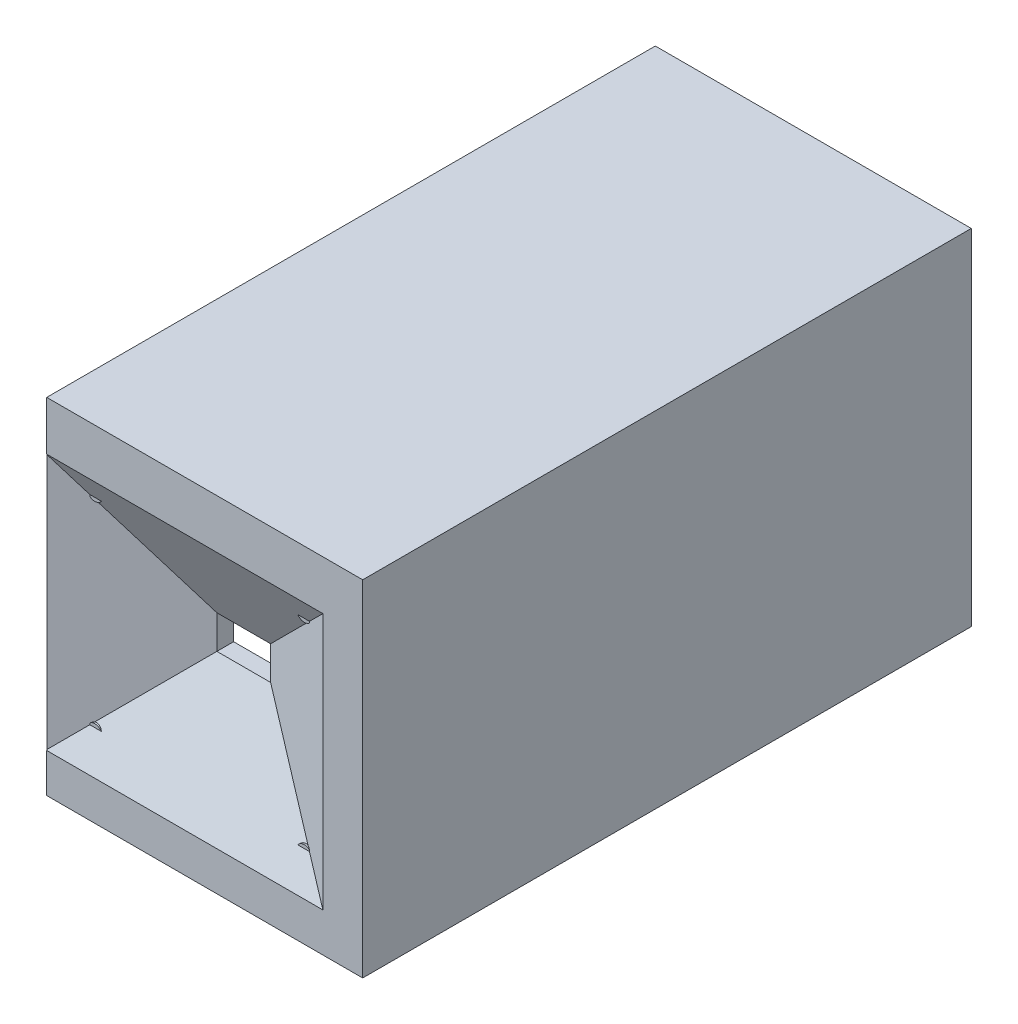
SolidWorks part; units mm, degrees
ref_plane "Front Plane" through (0, 0, 0) normal (0, 0, 1) x (1, 0, 0)
ref_plane "Top Plane" through (0, 0, 0) normal (0, 1, 0) x (1, 0, 0)
ref_plane "Right Plane" through (0, 0, 0) normal (1, 0, 0) x (0, 0, -1)
sketch "Sketch1" plane through (0, 0, 0) normal (0, 0, 1) x (1, 0, 0)
  line L10 (0, 0) -> (13.075, 0)
  line L15 (-13.575, -13.5) -> (-13.575, 13.5)
  line L16 (-13.575, 13.5) -> (13.575, 13.5)
  line L21 (13.575, -13.5) -> (13.575, 13.5)
  line L22 (-13.575, -13.5) -> (13.575, -13.5)
  line L28 (-12.425, -3.5) -> (-12.425, 3.5)
  line L29 (-12.425, 3.5) -> (-7.125, 3.5)
  line L30 (-7.125, -3.5) -> (-7.125, 3.5)
  line L31 (-12.425, -3.5) -> (-7.125, -3.5)
  line L32 (12.425, -3.5) -> (7.125, -3.5)
  line L33 (7.125, -3.5) -> (7.125, 3.5)
  line L34 (12.425, -3.5) -> (12.425, 3.5)
  line L35 (12.425, 3.5) -> (7.125, 3.5)
  line L36 (-2.65, -1.65) -> (-2.65, 1.65)
  line L37 (-2.65, 1.65) -> (2.65, 1.65)
  line L38 (2.65, -1.65) -> (2.65, 1.65)
  line L39 (-2.65, -1.65) -> (2.65, -1.65)
  circle A5 centre (10.325, 10.25) radius 0.762
  circle A6 centre (10.325, -10.25) radius 0.762
  circle A7 centre (-10.325, -10.25) radius 0.762
  circle A8 centre (-10.325, 10.25) radius 0.762
  point P0 (0, 0)
  point P16 (0, 0)
  point P31 (-9.775, 0)
  dimension "D10" = 1.524
  dimension "D11" = 1.524
  dimension "D12" = 1.524
  dimension "D13" = 1.524
  dimension "D18" = 13.075
ref_plane "Plane1" through (0, 0, 0) normal (0, 0, 1) x (1, 0, 0)
sketch "Sketch2" plane through (0, 0, 0) normal (0, 0, 1) x (1, 0, 0)
  line L0 (-16.575, 16.5) -> (-16.575, -16.5)
  line L5 (-16.575, -16.5) -> (16.575, -16.5)
  line L6 (16.575, 16.5) -> (16.575, -16.5)
  line L7 (-16.575, 16.5) -> (16.575, 16.5)
extrude "Boss-Extrude1" add sketch "Sketch2" along normal blind 7.5
ref_plane "Plane2" through (0, 0, 0) normal (0, 0, 1) x (1, 0, 0)
sketch "Sketch3" plane through (0, 0, 0) normal (0, 0, 1) x (1, 0, 0)
  circle A0 centre (10.325, 10.25) radius 0.762
  circle A1 centre (-10.325, 10.25) radius 0.762
  circle A2 centre (10.325, -10.25) radius 0.762
  circle A3 centre (-10.325, -10.25) radius 0.762
  dimension "D1" = 1.524
  dimension "D2" = 1.524
  dimension "D3" = 1.524
  dimension "D4" = 1.524
extrude "Cut-Extrude1" cut sketch "Sketch3" along normal blind 6
ref_plane "Plane3" through (0, 0, 0) normal (0, 0, 1) x (1, 0, 0)
sketch "Sketch4" plane through (0, 0, 0) normal (0, 0, 1) x (1, 0, 0)
  line L1 (12.425, -3.5) -> (7.125, -3.5)
  line L2 (12.425, -3.5) -> (12.425, 3.5)
  line L3 (12.425, 3.5) -> (7.125, 3.5)
  line L4 (7.125, -3.5) -> (7.125, 3.5)
  line L5 (-7.125, -3.5) -> (-12.425, -3.5)
  line L6 (-7.125, -3.5) -> (-7.125, 3.5)
  line L7 (-7.125, 3.5) -> (-12.425, 3.5)
  line L8 (-12.425, -3.5) -> (-12.425, 3.5)
extrude "Cut-Extrude2" cut sketch "Sketch4" along normal blind 3.4
ref_plane "Plane4" through (0, 0, 0) normal (0, 0, 1) x (1, 0, 0)
sketch "Sketch5" plane through (0, 0, 0) normal (0, 0, 1) x (1, 0, 0)
  line L1 (8.5467, -12.7134) -> (-8.766, -12.7134)
  line L2 (8.5467, -12.7134) -> (8.5467, -10.9049)
  line L3 (8.5467, -10.9049) -> (-8.766, -10.9049)
  line L4 (-8.766, -12.7134) -> (-8.766, -10.9049)
extrude "Cut-Extrude3" cut sketch "Sketch5" along normal blind 2
ref_plane "Plane5" through (0, 0, 0) normal (0, 0, 1) x (1, 0, 0)
sketch "Sketch6" plane through (0, 0, 0) normal (0, 0, 1) x (1, 0, 0)
  line L1 (2.65, -1.65) -> (-2.65, -1.65)
  line L2 (2.65, -1.65) -> (2.65, 1.65)
  line L3 (2.65, 1.65) -> (-2.65, 1.65)
  line L4 (-2.65, -1.65) -> (-2.65, 1.65)
extrude "Cut-Extrude4" cut sketch "Sketch6" along normal through all
chamfer "Chamfer3" distance 11 angle 28 4 edges at (-2.65, 0, 7.5) (0, -1.65, 7.5) (2.65, 0, 7.5) (0, 1.65, 7.5)
ref_plane "Plane7" through (0, 0, 0) normal (0, 0, 1) x (1, 0, 0)
sketch "Sketch7" plane through (0, 0, 0) normal (0, 0, 1) x (1, 0, 0)
  line L0 (16.575, 16.5) -> (-16.575, 16.5) construction
  line L1 (16.575, -16.5) -> (13.575, -16.5)
  line L3 (16.575, 16.5) -> (13.575, 16.5)
  line L4 (13.575, -16.5) -> (13.575, 16.5)
  line L5 (16.575, 16.5) -> (17.575, 16.5)
  line L6 (13.575, 13.5) -> (-16.575, 13.5)
  line L7 (13.575, 13.5) -> (13.575, 16.5)
  line L8 (13.575, 16.5) -> (-16.575, 16.5)
  line L9 (-16.575, 13.5) -> (-16.575, 16.5)
  line L10 (-13.575, 13.5) -> (-16.575, 13.5)
  line L11 (-13.575, 13.5) -> (-13.575, -16.5)
  line L12 (-13.575, -16.5) -> (-16.575, -16.5)
  line L13 (-16.575, 13.5) -> (-16.575, -16.5)
  line L14 (17.575, 16.5) -> (17.575, -16.5)
  line L15 (17.575, -16.5) -> (16.575, -16.5)
  dimension "D1" = 3
  dimension "D2" = 1
extrude "Boss-Extrude2" add sketch "Sketch7" against normal blind 52.5
sketch "Sketch8" plane through (0, 16.5, 0) normal (0, 1, 0) x (1, 0, 0)
  line L1 (-16.575, -7.5) -> (16.575, -7.5)
  line L2 (-16.575, -7.5) -> (-16.575, 52.5)
  line L3 (-16.575, 52.5) -> (16.575, 52.5)
  line L4 (16.575, -7.5) -> (16.575, 52.5)
extrude "Boss-Extrude3" add sketch "Sketch8" along normal blind 1
sketch "Sketch9" plane through (0, 0, -52.5) normal (0, 0, -1) x (-1, 0, 0)
  line L1 (13.575, -16.5) -> (16.575, -16.5)
  line L2 (13.575, -16.5) -> (13.575, 17.5)
  line L3 (13.575, 17.5) -> (16.575, 17.5)
  line L4 (16.575, -16.5) -> (16.575, 17.5)
extrude "Cut-Extrude5" cut sketch "Sketch9" against normal up to surface (60 mm away)
sketch "Sketch10" plane through (-13.575, 0, 0) normal (-1, 0, 0) x (0, 0, 1)
  line L0 (7.5, 17.5) -> (-52.5, 17.5) construction
  line L1 (-52.5, 17.5) -> (-52.5, 13.5) construction
  line L2 (7.5, -16.5) -> (0, -16.5) construction
  line L4 (7.5, 12.65) -> (7.5, 17.5) construction
  circle A0 centre (-44, 15.5) radius 0.762
  circle A1 centre (5, 11) radius 0.762
  circle A2 centre (5, -10) radius 0.762
  dimension "D2" = 1.524
  dimension "D1" = 2
  dimension "D3" = 8.5
  dimension "D4" = 6.5
  dimension "D5" = 6.5
  dimension "D6" = 2.5
extrude "Cut-Extrude6" cut sketch "Sketch10" against normal blind 6
sketch "Sketch11" plane through (0, -16.5, 0) normal (0, -1, 0) x (-1, 0, 0)
  line L0 (-16.575, -7.5) -> (-16.575, 0) construction
  line L1 (-17.575, 52.5) -> (-13.575, 52.5) construction
  line L2 (-16.575, -3.75) -> (5.2939, -3.75) construction
  line L4 (13.575, -7.5) -> (13.575, 0) construction
  line L5 (-17.575, 52.5) -> (-17.575, 0) construction
  line L6 (13.575, -7.5) -> (-16.575, -7.5) construction
  circle A0 centre (-15.575, 44) radius 0.762
  circle A1 centre (-15.575, -51.5) radius 0.762
  circle A2 centre (7.075, -4.5) radius 0.762
  circle A3 centre (-11.075, -4.5) radius 0.762
  dimension "D1" = 1.524
  dimension "D5" = 1.524
  dimension "D6" = 1.524
  dimension "D2" = 1
  dimension "D3" = 8.5
  dimension "D4" = 6.5
  dimension "D7" = 6.5
  dimension "D8" = 3
extrude "Cut-Extrude7" cut sketch "Sketch11" against normal blind 6
sketch "Sketch12" plane through (0, 0, -52.5) normal (0, 0, -1) x (-1, 0, 0)
  line L0 (-16.575, 17.5) -> (13.575, 17.5) construction
  line L2 (-17.575, -16.5) -> (-13.575, -16.5) construction
  line L3 (13.575, 17.5) -> (13.575, 13.5) construction
  line L4 (-17.575, 16.5) -> (-17.575, -16.5) construction
  circle A0 centre (-15.575, 15.5) radius 0.762
  circle A1 centre (-15.575, -14.5) radius 0.762
  circle A2 centre (11.575, 15.5) radius 0.762
  dimension "D3" = 1.524
  dimension "D6" = 1.524
  dimension "D7" = 1.524
  dimension "D1" = 2
  dimension "D2" = 2
  dimension "D4" = 2
  dimension "D5" = 2
  dimension "D8" = 2
  dimension "D9" = 2
extrude "Cut-Extrude9" cut sketch "Sketch12" against normal blind 7
sketch "Sketch13" plane through (13.575, 0, 0) normal (-1, 0, 0) x (0, 0, 1)
  line L0 (-52.5, -16.5) -> (-52.5, 13.5) construction
  line L1 (-52.5, 7) -> (-46.5, 7)
  line L2 (-52.5, 7) -> (-52.5, -13)
  line L3 (-52.5, -13) -> (-46.5, -13)
  line L4 (-46.5, 7) -> (-46.5, -13)
  line L5 (-52.5, -16.5) -> (0, -16.5) construction
  line L7 (-46.5, -13) -> (-43.5, -13)
  line L8 (-46.5, -13) -> (-46.5, -8)
  line L9 (-46.5, -8) -> (-43.5, -8)
  line L10 (-43.5, -13) -> (-43.5, -8)
  line M8 (-52.5, 13.5) -> (-52.5, -16.5)
  dimension "D1" = 3.5
  dimension "D2" = 20
  dimension "D3" = 6
  dimension "D4" = 3
  dimension "D5" = 5
extrude "Cut-Extrude10" cut sketch "Sketch13" against normal blind 1.5 contours L4 L1 L3 M8 | L7 L10 L9 L4
sketch "Sketch14" plane through (16.575, 0, 0) normal (1, 0, 0) x (0, 0, -1)
  line L0 (0, 17.1325) -> (0, -17.1325) construction
  line L1 (-7.5, 17.5) -> (0, 17.5)
  line L2 (-7.5, 17.5) -> (-7.5, -16.5)
  line L3 (-7.5, -16.5) -> (0, -16.5)
  line L4 (0, 17.5) -> (0, -16.5)
  line L5 (52.5, -16.5) -> (0, -16.5) construction
  line L6 (0, 16.5) -> (52.5, 16.5) construction
  line L7 (52.5, 17.5) -> (0, 17.5)
  line L8 (52.5, 17.5) -> (52.5, 16.5)
  line L9 (52.5, 16.5) -> (0, 16.5)
  line L10 (0, 17.5) -> (0, 16.5)
  line M1 (0, -16.5) -> (0, 16.5)
  line M2 (0, 16.5) -> (52.5, 16.5)
  line M3 (52.5, 16.5) -> (52.5, 17.5)
  line M4 (52.5, 17.5) -> (-7.5, 17.5)
  line M5 (-7.5, 17.5) -> (-7.5, -16.5)
  line M6 (-7.5, -16.5) -> (0, -16.5)
extrude "Boss-Extrude4" add sketch "Sketch14" along normal blind 1 contours L4 M4 M5 M6 M1 | L4 M4 M2 M3
sketch "Sketch15" plane through (0, 13.5, 0) normal (0, -1, 0) x (1, 0, 0)
  line L1 (-10.813, -6.776) -> (-10.813, -8.3) construction
  line L2 (-10.813, -8.3) -> (-11.575, -7.538) construction
  line L3 (-11.575, -7.538) -> (-10.051, -7.538) construction
  line L4 (17.1325, 0) -> (-17.1325, 0) construction
  line L5 (-13.575, -52.5) -> (-13.575, 0) construction
  line L6 (9.915, -22.458) -> (11.439, -22.458) construction
  line L7 (11.439, -22.458) -> (10.677, -21.696) construction
  line L8 (10.677, -21.696) -> (10.677, -23.22) construction
  line L9 (13.575, -52.5) -> (-13.575, -52.5) construction
  line L10 (13.575, -52.5) -> (13.575, 0) construction
  circle A0 centre (-10.813, -7.538) radius 0.762
  circle A1 centre (10.677, -22.458) radius 0.762
  dimension "D1" = 1.524
  dimension "D2" = 1.524
  dimension "D6" = 3.66
  dimension "D3" = 8.3
  dimension "D4" = 2
  dimension "D5" = 29.28
extrude "Cut-Extrude11" cut sketch "Sketch15" against normal blind 3.5
